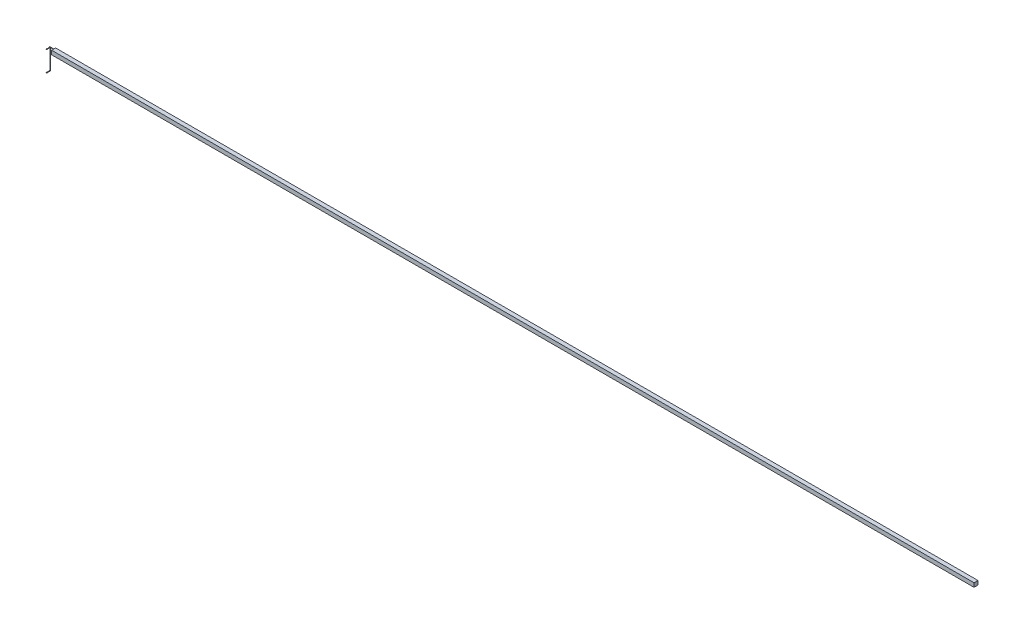
SolidWorks part; units mm, degrees
ref_plane "Plan de face" through (0, 0, 0) normal (0, 0, 1) x (1, 0, 0)
ref_plane "Plan de dessus" through (0, 0, 0) normal (0, 1, 0) x (1, 0, 0)
ref_plane "Plan de droite" through (0, 0, 0) normal (1, 0, 0) x (0, 0, -1)
sketch "Esquisse2" plane through (0, 0, 0) normal (0, 0, 1) x (1, 0, 0)
  line L0 (72, 86) -> (7072, 86)
  line L1 (71, 86) -> (71, -68)
  circle A0 centre (72, 86) radius 3 construction
  circle A1 centre (72, 86) radius 3
  circle A2 centre (71, -68) radius 3
  dimension "D1" = 1
  dimension "D2" = 154
  dimension "D3" = 7000
ref_plane "Plan2" through (71, 86, 0) normal (0, -1, 0) x (-1, 0, 0)
sketch "Esquisse7" plane through (71, 86, 0) normal (0, -1, 0) x (-1, 0, 0)
  line L0 (-7001, 0) -> (-41, 0)
  line L1 (-1, 0) -> (-7001, 0) construction
  line L2 (-41, 0) -> (-41, 15)
  line L3 (-41, 15) -> (-1, 15)
  line L4 (-1, 15) -> (-1, -15)
  dimension "D1" = 40
  dimension "D2" = 15
  dimension "D3" = 30
ref_plane "Plan3" through (72, 86, 15) normal (0, 0, 1) x (1, 0, 0)
sketch "Esquisse8" plane through (72, 86, 15) normal (0, 0, 1) x (1, 0, 0)
  circle A0 centre (0, 0) radius 1.5
  dimension "D1" = 3
sweep "Balayage1" add profiles "Esquisse8" path "Esquisse7"
sketch "Esquisse9" plane through (71, 86, 0) normal (0, -1, 0) x (-1, 0, 0)
  line L0 (-1, -10) -> (-1, 10) construction
  line L1 (2, 10) -> (-4, 10) construction
  line L2 (-4, -10) -> (2, -10) construction
  line L4 (-1, -10) -> (2, -10)
  line L5 (-1, -10) -> (-1, -11)
  line L6 (-1, -11) -> (2, -11)
  line L7 (2, -10) -> (2, -11)
  line L8 (-1, 10) -> (2, 10)
  line L9 (-1, 10) -> (-1, 11)
  line L10 (-1, 11) -> (2, 11)
  line L11 (2, 10) -> (2, 11)
  dimension "D1" = 1
revolve "Révolution1" add sketch "Esquisse9" angle 360 about L0
ref_plane "Plan1" through (71, 0, 0) normal (1, 0, 0) x (0, 0, -1)
sketch "Esquisse10" plane through (71, 0, 0) normal (1, 0, 0) x (0, 0, -1)
  line L0 (-15, -68) -> (15, -68)
  line L1 (15, -68) -> (15, 86)
ref_plane "Plan4" through (71, -68, 15) normal (0, 0, -1) x (-1, 0, 0)
sketch "Esquisse11" plane through (71, -68, 15) normal (0, 0, -1) x (-1, 0, 0)
  circle A0 centre (0, 0) radius 1.5
  dimension "D1" = 3
sweep "Balayage2" add profiles "Esquisse11" path "Esquisse10"
sketch "Esquisse12" plane through (71, 0, 0) normal (1, 0, 0) x (0, 0, -1)
  line L0 (-15, -68) -> (15, -68) construction
  line L1 (10, -68) -> (9, -68)
  line L2 (10, -68) -> (10, -65)
  line L3 (10, -65) -> (9, -65)
  line L4 (9, -68) -> (9, -65)
  line L5 (-9, -65) -> (-10, -65)
  line L6 (-9, -65) -> (-9, -68)
  line L7 (-9, -68) -> (-10, -68)
  line L8 (-10, -65) -> (-10, -68)
  line L9 (10, -68) -> (-10, -68) construction
  dimension "D1" = 1
revolve "Révolution2" add sketch "Esquisse12" angle 360 about L9
sketch "Esquisse14" plane through (71, 0, 0) normal (1, 0, 0) x (0, 0, -1)
  circle A0 centre (15, 86) radius 1.5
  dimension "D1" = 3
extrude "Boss.-Extru.4" add sketch "Esquisse14" along normal mid plane 5
sketch "Esquisse15" plane through (7072, 0, 0) normal (1, 0, 0) x (0, 0, -1)
  line L0 (15, 101) -> (-15, 71) construction
  line L1 (-15, 101) -> (15, 101)
  line L2 (-15, 101) -> (-15, 71)
  line L3 (-15, 71) -> (15, 71)
  line L4 (15, 101) -> (15, 71)
  dimension "D1" = 30
extrude "Boss.-Extru.5" add sketch "Esquisse15" against normal up to vertex (6960 mm away) up to point (112, 86, 0)
